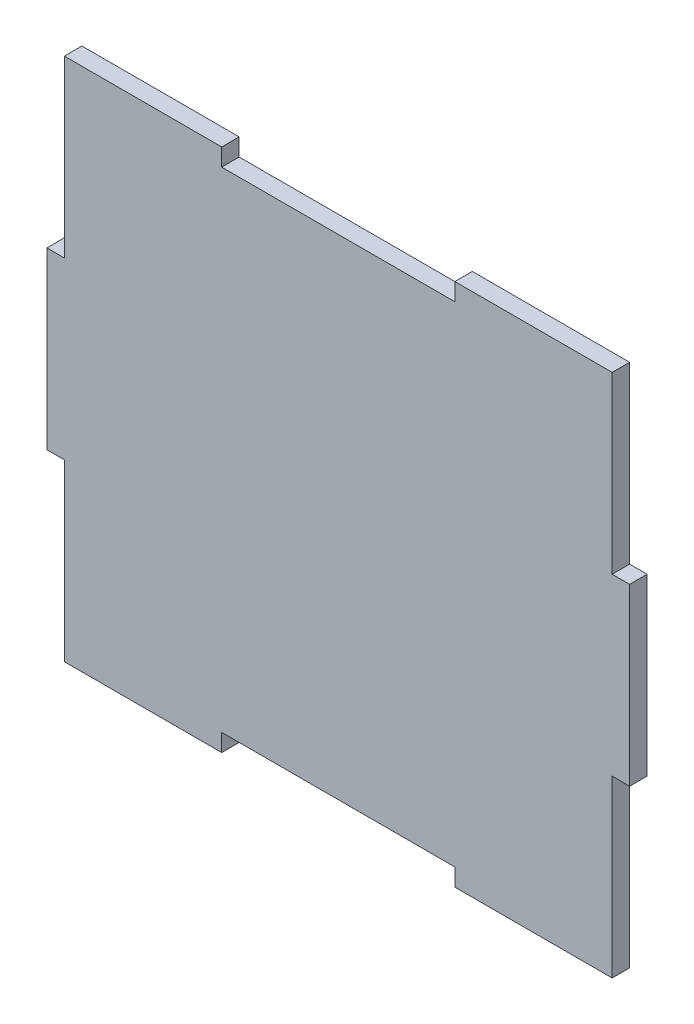
SolidWorks part; units mm, degrees
ref_plane "Plan de face" through (0, 0, 0) normal (0, 0, 1) x (1, 0, 0)
ref_plane "Plan de dessus" through (0, 0, 0) normal (0, 1, 0) x (1, 0, 0)
ref_plane "Plan de droite" through (0, 0, 0) normal (1, 0, 0) x (0, 0, -1)
sketch "Esquisse1" plane through (0, 0, 0) normal (0, 0, 1) x (1, 0, 0)
  line L1 (-60.0385, 25.677) -> (39.9615, 25.677)
  line L2 (-60.0385, 25.677) -> (-60.0385, -64.323)
  line L3 (-60.0385, -64.323) -> (39.9615, -64.323)
  line L4 (39.9615, 25.677) -> (39.9615, -64.323)
  dimension "D1" = 100
  dimension "D2" = 90
extrude "Boss.-Extru.1" add sketch "Esquisse1" along normal blind 3
sketch "Esquisse2" plane through (0, 0, 3) normal (0, 0, 1) x (1, 0, 0)
  line L0 (39.9615, 25.677) -> (-60.0385, 25.677) construction
  line L1 (-30.0385, 25.677) -> (9.9615, 25.677)
  line L2 (-30.0385, 25.677) -> (-30.0385, 22.677)
  line L3 (-30.0385, 22.677) -> (9.9615, 22.677)
  line L4 (9.9615, 25.677) -> (9.9615, 22.677)
  line L5 (-60.0385, 25.677) -> (-60.0385, -64.323) construction
  line L6 (-60.0385, 25.677) -> (-57.0385, 25.677)
  line L7 (-60.0385, 25.677) -> (-60.0385, -4.323)
  line L8 (-60.0385, -4.323) -> (-57.0385, -4.323)
  line L9 (-57.0385, 25.677) -> (-57.0385, -4.323)
  line L10 (-60.0385, -34.323) -> (-57.0385, -34.323)
  line L11 (-60.0385, -34.323) -> (-60.0385, -64.323)
  line L12 (-60.0385, -64.323) -> (-57.0385, -64.323)
  line L13 (-57.0385, -34.323) -> (-57.0385, -64.323)
  line L14 (-60.0385, -64.323) -> (39.9615, -64.323) construction
  line L15 (39.9615, -64.323) -> (39.9615, 25.677) construction
  line L16 (-30.0385, -64.323) -> (9.9615, -64.323)
  line L17 (-30.0385, -64.323) -> (-30.0385, -61.323)
  line L18 (-30.0385, -61.323) -> (9.9615, -61.323)
  line L19 (9.9615, -64.323) -> (9.9615, -61.323)
  line L20 (36.9615, -64.323) -> (39.9615, -64.323)
  line L21 (36.9615, -64.323) -> (36.9615, -34.323)
  line L22 (36.9615, -34.323) -> (39.9615, -34.323)
  line L23 (39.9615, -64.323) -> (39.9615, -34.323)
  line L25 (36.9615, 25.677) -> (39.9615, 25.677)
  line L26 (36.9615, 25.677) -> (36.9615, -4.323)
  line L27 (36.9615, -4.323) -> (39.9615, -4.323)
  line L28 (39.9615, 25.677) -> (39.9615, -4.323)
  dimension "D1" = 3
  dimension "D2" = 30
  dimension "D3" = 40
  dimension "D4" = 27
extrude "Enlèv. mat.-Extru.1" cut sketch "Esquisse2" against normal up to next
